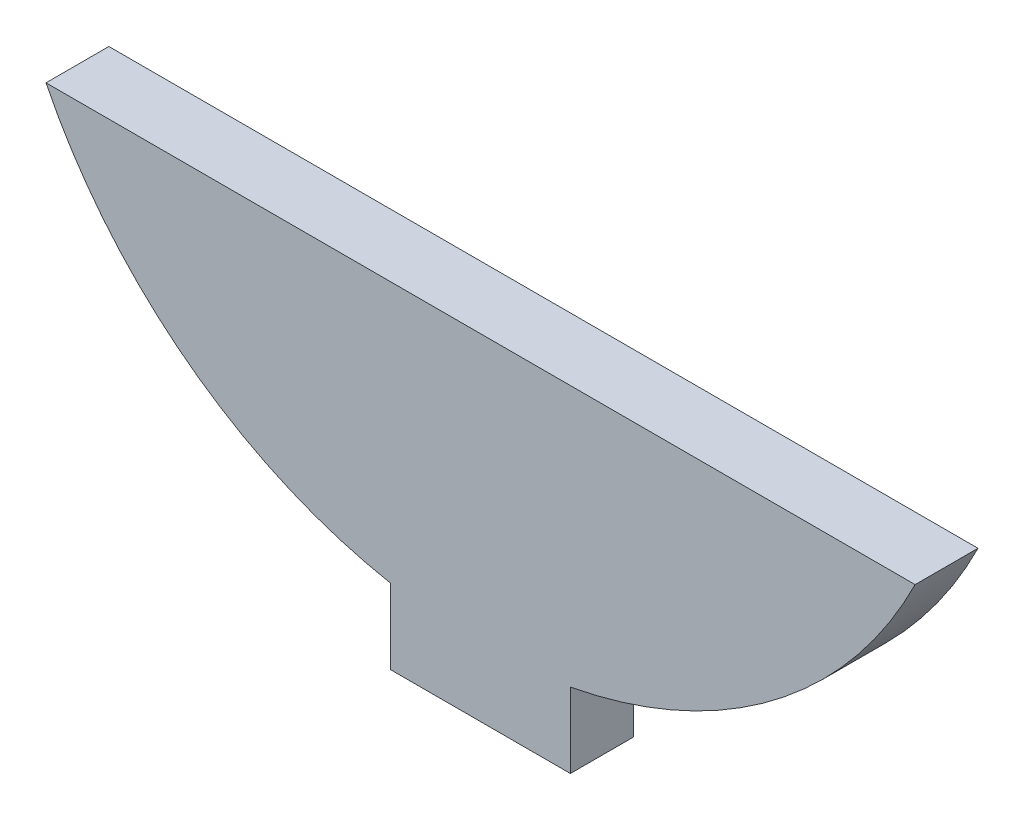
SolidWorks part; units mm, degrees
ref_plane "前视基准面" through (0, 0, 0) normal (0, 0, 1) x (1, 0, 0)
ref_plane "上视基准面" through (0, 0, 0) normal (0, 1, 0) x (1, 0, 0)
ref_plane "右视基准面" through (0, 0, 0) normal (1, 0, 0) x (0, 0, -1)
sketch "草图1" plane through (0, 0, 0) normal (0, 0, 1) x (1, 0, 0)
  line L0 (0, -55) -> (0, 55) construction
  line L1 (-24.1868, 16.6165) -> (24.1868, 16.6165)
  line L2 (5, -2.0835) -> (-5, -2.0835)
  line L3 (5, -2.0835) -> (5, 2.0835)
  line L4 (5, 2.0835) -> (-5, 2.0835) construction
  line L5 (-5, -2.0835) -> (-5, 2.0835)
  line L6 (5, -2.0835) -> (-5, 2.0835) construction
  line L7 (5, 2.0835) -> (-5, -2.0835) construction
  arc A0 (5, 2.0835) -> (-5, 2.0835) centre (0, 28.6165) ccw
  arc A1 (-5, 2.0835) -> (5, 2.0835) centre (0, 28.6165) ccw construction
  point P4 (0, 0)
  dimension "D1" = 54
  dimension "D2" = 10
  dimension "D3" = 30.7
  dimension "D4" = 18.7
extrude "凸台-拉伸1" add sketch "草图1" along normal blind 3.5 contours L1 A0 L5 L2 L3
